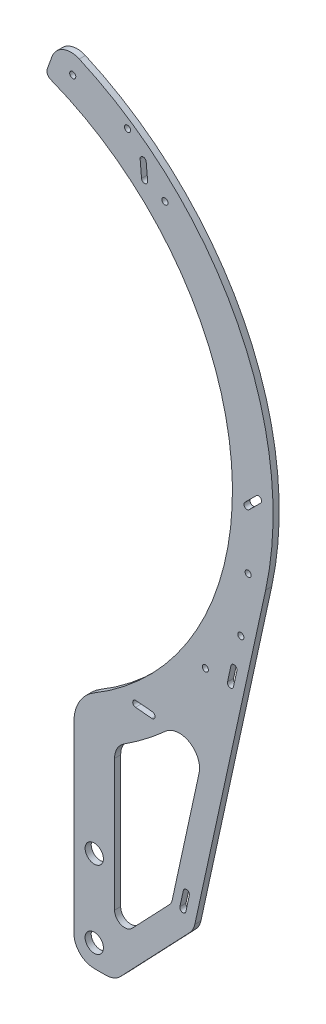
SolidWorks part; units mm, degrees
material "Thornel Mat VMA"
ref_plane "前视基准面" through (0, 0, 0) normal (0, 0, 1) x (1, 0, 0)
ref_plane "上视基准面" through (0, 0, 0) normal (0, 1, 0) x (1, 0, 0)
ref_plane "右视基准面" through (0, 0, 0) normal (1, 0, 0) x (0, 0, -1)
sketch "草图1" plane through (0, 0, 0) normal (0, 0, 1) x (1, 0, 0)
  line L0 (-10, 49) -> (-10, 100.9771)
  line L1 (-10, 49) -> (10, 49)
  line L2 (-10, 49) -> (-10, -11)
  line L3 (-10, -11) -> (10, -11)
  line L4 (10, 49) -> (10, -11)
  line L5 (-10, 49) -> (10, -11) construction
  line L6 (-10, -11) -> (10, 49) construction
  line L7 (10, 49) -> (10, 113.0275)
  line L8 (-72, 226.5) -> (-17.2768, 376.8508)
  line L9 (-72, 226.5) -> (-72, 386.5) construction
  circle A0 centre (0, 0) radius 4.5
  circle A1 centre (0, 38) radius 4.5
  circle A2 centre (-72, 226.5) radius 140
  circle A3 centre (-72, 226.5) radius 160
  point P5 (0, 19)
  dimension "D1" = 9
  dimension "D2" = 9
  dimension "D7" = 280
  dimension "D10" = 320
  dimension "D3" = 38
  dimension "D4" = 60
  dimension "D5" = 20
  dimension "D6" = 19
  dimension "D8" = 226.5
  dimension "D9" = 72
  dimension "D11" = 20
extrude "凸台-拉伸1" add sketch "草图1" along normal blind 3 contours L7 A3 L8 A2 | L0 A3 L7 A2 | A3 L0 L1 L7 | L4 L1 L2 L3 A1 A0
sketch "草图2" plane through (0, 0, 3) normal (0, 0, 1) x (1, 0, 0)
  line L0 (10, -11) -> (40, -11)
  line L1 (40, -11) -> (84.3312, 192.433)
  line L2 (10, -11) -> (10, -1)
  line L3 (10, -11) -> (10, 89.11) construction
  line L4 (10, -1) -> (30, -1)
  line L5 (30, -1) -> (59.8119, 135.8047)
  arc A0 (10, 89.11) -> (-17.2768, 376.8508) centre (-72, 226.5) ccw construction
  circle A1 centre (-72, 226.5) radius 160
  arc A2 (-10, 100.9771) -> (-24.1172, 358.057) centre (-72, 226.5) ccw construction
  line M6 (10, -11) -> (10, 89.11)
  arc M7 (10, 89.11) -> (-17.2768, 376.8508) centre (-72, 226.5) ccw
  dimension "D1" = 30
  dimension "D2" = 10
  dimension "D3" = 20
extrude "凸台-拉伸2" add sketch "草图2" against normal blind 3 contours L5 L4 L0 L1 M6 M7
fillet "圆角2" radius 20 1 edges at (-10, 100.9771, 1.5)
fillet "圆角3" radius 10 2 edges at (40, -11, 1.5) (-10, -11, 1.5)
fillet "圆角4" radius 3 1 edges at (-24.1172, 358.057, 1.5)
fillet "圆角5" radius 10 1 edges at (-17.2768, 376.8508, 1.5)
sketch "草图3" plane through (0, 0, 0) normal (0, 0, -1) x (-1, 0, 0)
  line L1 (-46.7784, 43.5889) -> (-43.8472, 44.2277)
  line L2 (-46.7784, 43.5889) -> (-45.0751, 35.7723)
  line L3 (-45.0751, 35.7723) -> (-42.1439, 36.4111)
  line L4 (-43.8472, 44.2277) -> (-42.1439, 36.4111)
  line L5 (-46.7784, 43.5889) -> (-42.1439, 36.4111) construction
  line L6 (-45.0751, 35.7723) -> (-43.8472, 44.2277) construction
  line L9 (-41.7152, -3.1292) -> (-84.3312, 192.433) construction
  line L10 (-70.1995, 151.0666) -> (-68.4961, 143.25)
  line L11 (-70.1995, 151.0666) -> (-67.2683, 151.7054)
  line L12 (-67.2683, 151.7054) -> (-65.5649, 143.8888)
  line L13 (-68.4961, 143.25) -> (-65.5649, 143.8888)
  point P0 (-44.4611, 40)
  dimension "D1" = 8
  dimension "D2" = 3
  dimension "D3" = 5
  dimension "D4" = 40
  dimension "D6" = 110
  dimension "D5" = 2
extrude "切除-拉伸1" cut sketch "草图3" against normal through all
sketch "草图4" plane through (0, 0, 0) normal (0, 0, -1) x (-1, 0, 0)
  line L0 (72, 226.5) -> (-78, 226.5) construction
  line L1 (72, 226.5) -> (-84.6648, 39.7942) construction
  line L3 (-28.2722, 109.7504) -> (-28.5337, 112.739)
  line L4 (-28.2722, 109.7504) -> (-20.3026, 110.4477)
  line L5 (-20.3026, 110.4477) -> (-20.5641, 113.4362)
  line L6 (-28.5337, 112.739) -> (-20.5641, 113.4362)
  line L7 (-28.2722, 109.7504) -> (-20.5641, 113.4362) construction
  line L8 (-20.3026, 110.4477) -> (-28.5337, 112.739) construction
  line L16 (-81.8891, 228.2678) -> (-76.2322, 222.6109)
  line L17 (-81.8891, 228.2678) -> (-79.7678, 230.3891)
  line L18 (-79.7678, 230.3891) -> (-74.1109, 224.7322)
  line L19 (-76.2322, 222.6109) -> (-74.1109, 224.7322)
  line L20 (-25.5638, 345.5222) -> (-26.2611, 337.5526)
  line L21 (-25.5638, 345.5222) -> (-22.5752, 345.2607)
  line L22 (-22.5752, 345.2607) -> (-23.2725, 337.2912)
  line L23 (-26.2611, 337.5526) -> (-23.2725, 337.2912)
  line L24 (100.4635, 377.7442) -> (93.9103, 373.1556)
  line L25 (100.4635, 377.7442) -> (102.1842, 375.2867)
  line L26 (102.1842, 375.2867) -> (95.631, 370.6981)
  line L27 (93.9103, 373.1556) -> (95.631, 370.6981)
  line L28 (72, 226.5) -> (-20.5641, 113.4362) construction
  line L29 (72, 226.5) -> (-74.1109, 224.7322) construction
  circle A0 centre (72, 226.5) radius 150 construction
  point P5 (-24.4181, 111.5933)
  dimension "D1" = 300
  dimension "D2" = 50
  dimension "D3" = 8
  dimension "D4" = 3
  dimension "D6" = 50
  dimension "D7" = 45
  dimension "D8" = 226.5
  dimension "D9" = 72
  dimension "D5" = 4
extrude "切除-拉伸2" cut sketch "草图4" against normal through all
sketch "草图5" plane through (0, 0, 3) normal (0, 0, 1) x (1, 0, 0)
  line L0 (-72, 599.9781) -> (-72, -121.148) construction
  line L1 (-72, 226.5) -> (205.1542, 111.699) construction
  line L2 (-72, 226.5) -> (75.7003, 195.1053) construction
  circle A0 centre (-72, 226.5) radius 151 construction
  circle A1 centre (-72, 226.5) radius 156 construction
  circle A2 centre (72.1252, 166.8014) radius 1.5
  circle A3 centre (75.7003, 195.1053) radius 1.5
  circle A4 centre (54.6393, 144.2595) radius 1.5
  circle A5 centre (34.7731, 333.2731) radius 1.5
  circle A6 centre (16.3594, 355.0637) radius 1.5
  circle A7 centre (-10.5828, 364.4454) radius 1.5
  point P21 (-72, 226.5)
  dimension "D1" = 302
  dimension "D2" = 312
  dimension "D4" = 3
  dimension "D6" = 3
  dimension "D3" = 67.5
  dimension "D5" = 10.5
  dimension "D7" = 2
extrude "切除-拉伸3" cut sketch "草图5" against normal through all
sketch "草图6" plane through (0, 0, 0) normal (0, 0, -1) x (-1, 0, 0)
  line L0 (-48.8958, 29.8224) -> (-37.2688, 32.3561)
  line L1 (-41.7152, -3.1292) -> (-84.3312, 192.433) construction
  line L2 (-30, -1) -> (-59.8119, 135.8047) construction
  line L3 (-45.0751, 35.7723) -> (-42.1439, 36.4111) construction
  line L4 (-48.8958, 29.8224) -> (-44.5443, -23.8406)
  line L5 (-44.5443, -23.8406) -> (-10, -25.4559)
  line L6 (-10, -25.4559) -> (-10, -1)
  line L7 (-10, -1) -> (-37.2688, 32.3561)
  dimension "D1" = 5
extrude "切除-拉伸4" cut sketch "草图6" against normal through all
sketch "草图7" plane through (0, 0, 0) normal (0, 0, -1) x (-1, 0, 0)
  line L0 (-48.8958, 29.8224) -> (-10, -11)
  line L1 (-38.0202, 35.804) -> (-10, 6.3959)
  line L2 (-37.2688, 32.3561) -> (-59.8119, 135.8047) construction
  line L3 (-10, -11) -> (-10, 89.11) construction
  line L4 (-38.0202, 35.804) -> (-37.2688, 32.3561)
  line L5 (-37.2688, 32.3561) -> (-48.8958, 29.8224)
  line L6 (-10, 6.3959) -> (-10, -11)
  dimension "D1" = 12
extrude "凸台-拉伸3" add sketch "草图7" against normal blind 3
fillet "圆角6" radius 10 4 edges at (59.8119, 135.8047, 1.5) (10, 89.11, 1.5) (48.8958, 29.8224, 1.5) (10, -11, 1.5)
fillet "圆角7" radius 5 2 edges at (38.0202, 35.804, 1.5) (10, 6.3959, 1.5)
sketch "草图8" plane through (0, 0, 0) normal (0, 0, -1) x (-1, 0, 0)
  line L0 (-45.0751, 35.7723) -> (-42.1439, 36.4111) construction
  line L1 (-43.8472, 44.2277) -> (-46.7784, 43.5889) construction
  line L2 (-68.4961, 143.25) -> (-65.5649, 143.8888) construction
  line L3 (-67.2683, 151.7054) -> (-70.1995, 151.0666) construction
  line L4 (-28.5337, 112.739) -> (-28.2722, 109.7504) construction
  line L5 (-20.3026, 110.4477) -> (-20.5641, 113.4362) construction
  line L6 (-76.2322, 222.6109) -> (-74.1109, 224.7322) construction
  line L7 (-79.7678, 230.3891) -> (-81.8891, 228.2678) construction
  line L8 (-26.2611, 337.5526) -> (-23.2725, 337.2912) construction
  line L9 (-22.5752, 345.2607) -> (-25.5638, 345.5222) construction
  circle A0 centre (-43.6095, 36.0917) radius 1.5
  circle A1 centre (-45.3128, 43.9083) radius 1.5
  circle A2 centre (-67.0305, 143.5694) radius 1.5
  circle A3 centre (-68.7339, 151.386) radius 1.5
  circle A4 centre (-28.4029, 111.2447) radius 1.5
  circle A5 centre (-20.4334, 111.942) radius 1.5
  circle A6 centre (-75.1716, 223.6716) radius 1.5
  circle A7 centre (-80.8284, 229.3284) radius 1.5
  circle A8 centre (-24.7668, 337.4219) radius 1.5
  circle A9 centre (-24.0695, 345.3914) radius 1.5
extrude "切除-拉伸5" cut sketch "草图8" against normal through all
